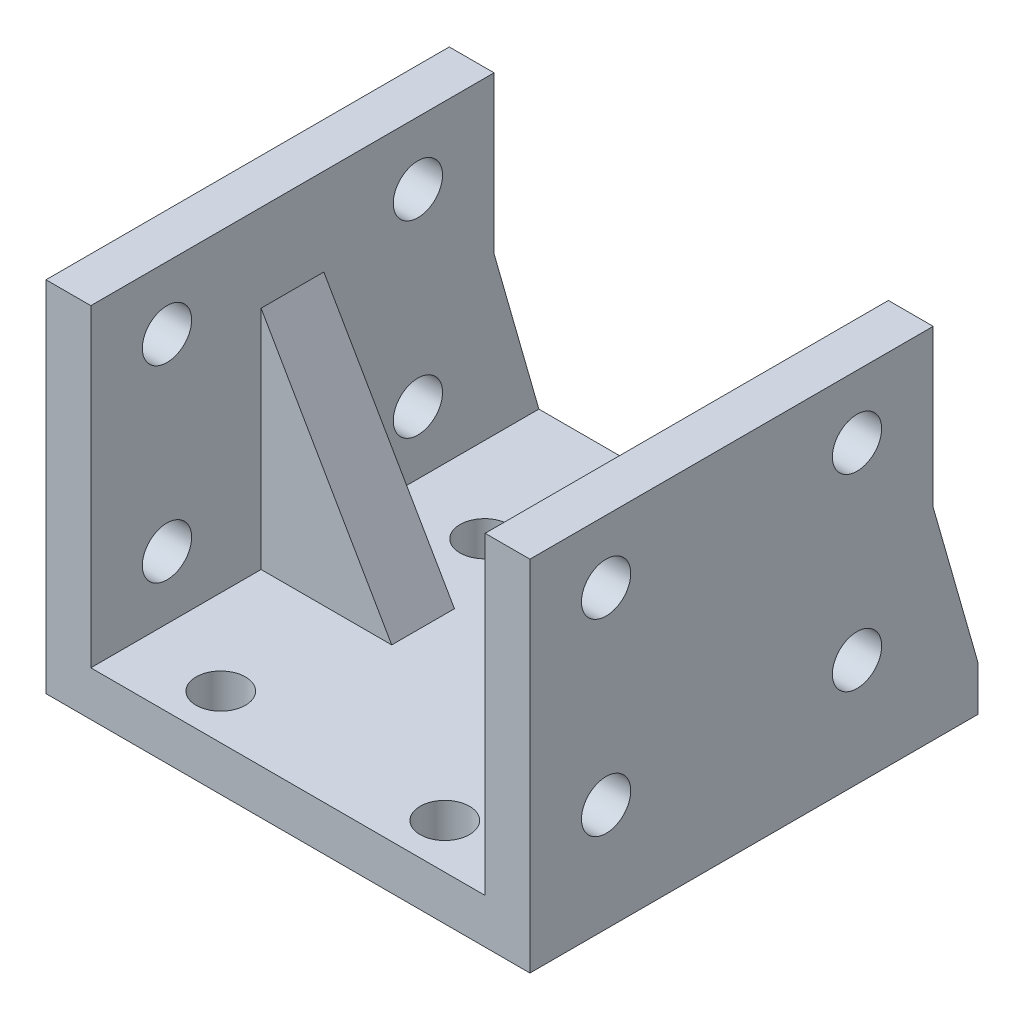
SolidWorks part; units mm, degrees
ref_plane "Front Plane" through (0, 0, 0) normal (0, 0, 1) x (1, 0, 0)
ref_plane "Top Plane" through (0, 0, 0) normal (0, 1, 0) x (1, 0, 0)
ref_plane "Right Plane" through (0, 0, 0) normal (1, 0, 0) x (0, 0, -1)
sketch "Sketch1" plane through (0, 0, 0) normal (0, 1, 0) x (1, 0, 0)
  line L1 (-27, 27.5) -> (27, 27.5)
  line L2 (-27, 27.5) -> (-27, -27.5)
  line L3 (-27, -27.5) -> (27, -27.5)
  line L4 (27, 27.5) -> (27, -27.5)
  line L5 (-27, 27.5) -> (27, -27.5) construction
  line L6 (-27, -27.5) -> (27, 27.5) construction
  point P0 (0, 0)
  dimension "D1" = 54
  dimension "D2" = 55
extrude "Boss-Extrude1" add sketch "Sketch1" along normal blind 5
sketch "Sketch6" plane through (0, 5, 0) normal (0, 1, 0) x (1, 0, 0)
  line L0 (-27, 27.5) -> (-27, -27.5) construction
  line L1 (-27, 22.5) -> (-22, 22.5)
  line L2 (-27, 22.5) -> (-27, -22.5)
  line L3 (-27, -22.5) -> (-22, -22.5)
  line L4 (-22, 22.5) -> (-22, -22.5)
  point P6 (-22, 0)
  dimension "D1" = 5
  dimension "D2" = 45
extrude "Boss-Extrude3" add sketch "Sketch6" along normal blind 35
sketch "Sketch7" plane through (-22, 0, 0) normal (1, 0, 0) x (0, 0, -1)
  line L0 (22.5, 40) -> (22.5, 5) construction
  line L1 (-14, 33) -> (14, 33) construction
  line L2 (-14, 33) -> (-14, 12) construction
  line L3 (-14, 12) -> (14, 12) construction
  line L4 (14, 33) -> (14, 12) construction
  circle A0 centre (-14, 33) radius 2.75
  circle A1 centre (14, 33) radius 2.75
  circle A2 centre (14, 12) radius 2.75
  circle A3 centre (-14, 12) radius 2.75
  point P8 (0, 12)
  point P10 (14, 22.5)
  point P13 (22.5, 22.5)
  dimension "D1" = 5.5
  dimension "D2" = 5.5
  dimension "D3" = 5.5
  dimension "D4" = 5.5
  dimension "D5" = 28
  dimension "D6" = 21
extrude "Cut-Extrude2" cut sketch "Sketch7" against normal through all
sketch "Sketch8" plane through (-27, 0, 0) normal (-1, 0, 0) x (0, 0, 1)
  line L0 (-22.5, 22.5) -> (-27.5, 5)
  line L1 (-22.5, 40) -> (-22.5, 5) construction
rib "Rib1" sketch "Sketch8" sketch "Sketch8" thickness 5 extrusion direction parallel to sketch draft on no parameters "D1"=5
mirror "Mirror1" about plane through (0, 0, 0) normal (0, 0, 1) of "Rib1"
mirror "Mirror2" about plane through (0, 0, 0) normal (1, 0, 0) of "Mirror1", "Rib1", "Cut-Extrude2", "Boss-Extrude3"
sketch "Sketch9" plane through (0, 0, 0) normal (0, 0, 1) x (1, 0, 0)
  line L0 (-22, 30.25) -> (-7.4219, 5)
  line L1 (-22, 5) -> (22, 5) construction
  dimension "D1" = 60
rib "Rib4" sketch "Sketch9" sketch "Sketch9" thickness 7 extrusion direction parallel to sketch draft on no parameters "D1"=7
mirror "Mirror3" about plane through (0, 0, 0) normal (1, 0, 0) of "Rib4"
sketch "Sketch10" plane through (0, 5, 0) normal (0, 1, 0) x (1, 0, 0)
  line L1 (12.5, 11.9432) -> (-12.5, 11.9432) construction
  line L2 (12.5, 11.9432) -> (12.5, -17.5) construction
  line L3 (12.5, -17.5) -> (-12.5, -17.5) construction
  line L4 (-12.5, 11.9432) -> (-12.5, -17.5) construction
  circle A0 centre (12.5, 11.9432) radius 2.75
  circle A1 centre (12.5, -17.5) radius 2.75
  circle A2 centre (-12.5, -17.5) radius 2.75
  circle A3 centre (-12.5, 11.9432) radius 2.75
  point P0 (0, 0)
  dimension "D1" = 5.5
  dimension "D2" = 25
extrude "Cut-Extrude3" cut sketch "Sketch10" against normal through all
sketch "Sketch11" plane through (0, 0, 0) normal (0, -1, 0) x (1, 0, 0)
  line L0 (27, 27.5) -> (27, -27.5) construction
  line L1 (-27, 27.5) -> (27, 27.5)
  line L2 (-27, 27.5) -> (-27, 22.5)
  line L3 (-27, 22.5) -> (27, 22.5)
  line L4 (27, 27.5) -> (27, 22.5)
  dimension "D1" = 5
extrude "Cut-Extrude4" cut sketch "Sketch11" against normal blind 40
